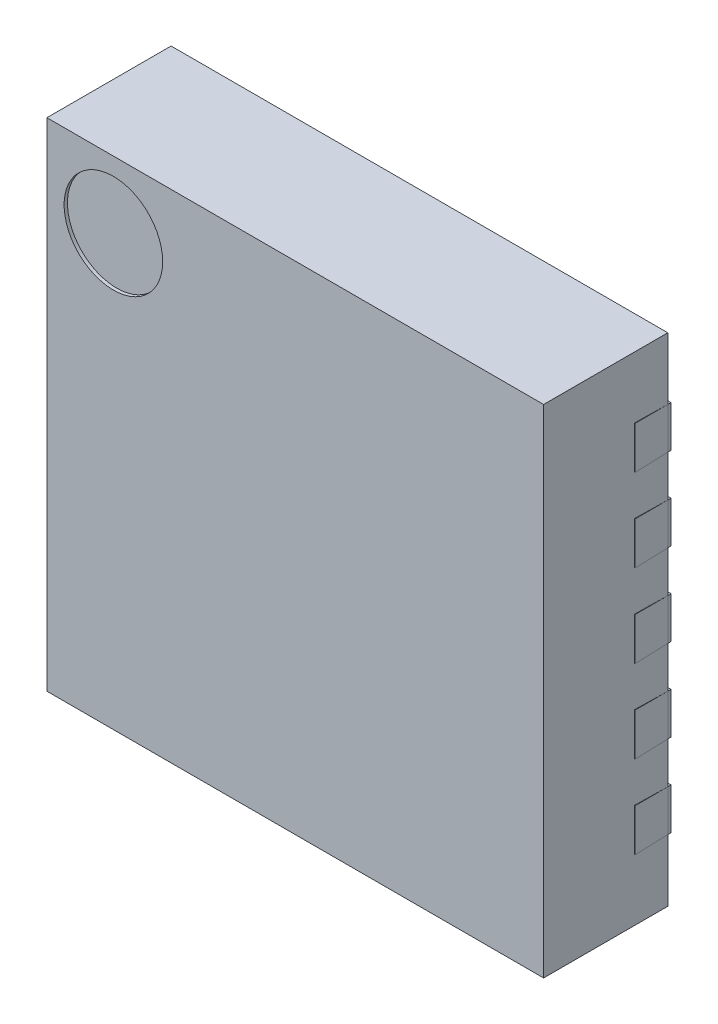
SolidWorks part; units mm, degrees
ref_plane "Front Plane" through (0, 0, 0) normal (0, 0, 1) x (1, 0, 0)
ref_plane "Top Plane" through (0, 0, 0) normal (0, 1, 0) x (1, 0, 0)
ref_plane "Right Plane" through (0, 0, 0) normal (1, 0, 0) x (0, 0, -1)
sketch "Sketch1" plane through (0, 0, 0) normal (0, 0, 1) x (1, 0, 0)
  line L1 (-1.5, -1.5) -> (1.5, -1.5)
  line L2 (-1.5, -1.5) -> (-1.5, 1.5)
  line L3 (-1.5, 1.5) -> (1.5, 1.5)
  line L4 (1.5, -1.5) -> (1.5, 1.5)
  line L5 (-1.5, -1.5) -> (1.5, 1.5) construction
  line L6 (-1.5, 1.5) -> (1.5, -1.5) construction
  point P0 (0, 0)
  dimension "D1" = 3
  dimension "D2" = 3
extrude "Boss-Extrude1" add sketch "Sketch1" along normal blind 0.75
sketch "Sketch2" plane through (0, 0, 0.75) normal (0, 0, 1) x (1, 0, 0)
  circle A0 centre (-1.0984, 1.0966) radius 0.2976
  point P2 (-1.0984, 1.0966)
extrude "Cut-Extrude1" cut sketch "Sketch2" against normal blind 0.02
sketch "Sketch3" plane through (0, 0, 0) normal (0, 0, -1) x (-1, 0, 0)
  line L0 (0.825, 1.0076) -> (0.6426, 1.19)
  line L1 (-0.825, -1.19) -> (0.825, -1.19)
  line L2 (-0.825, -1.19) -> (-0.825, 1.19)
  line L3 (-0.825, 1.19) -> (0.6426, 1.19)
  line L4 (0.825, -1.19) -> (0.825, 1.0076)
  line L5 (-0.825, -1.19) -> (0.7503, 1.0823) construction
  line L6 (-0.825, 1.19) -> (0.825, -1.19) construction
  point P0 (0, 0)
extrude "Boss-Extrude2" add sketch "Sketch3" along normal blind 0.02
sketch "Sketch4" plane through (0, 0, 0) normal (0, 0, -1) x (-1, 0, 0)
  line L0 (-1.5, -1.5) -> (-1.5, 1.5) construction
  line L1 (-1.5, 0.125) -> (-1.245, 0.125)
  line L3 (-1.5, -0.125) -> (-1.245, -0.125)
  line L5 (0, 0) -> (-1.5, 0) construction
  line L6 (-1.5, 0) -> (-1.12, 0) construction
  line L7 (-1.5, 0.125) -> (-1.5, -0.125)
  arc A0 (-1.245, -0.125) -> (-1.245, 0.125) centre (-1.245, 0) ccw
  point P0 (-1.5, 0)
  point P4 (-1.5, 0)
  dimension "D2" = 0.25
  dimension "D1" = 0.255
extrude "Boss-Extrude3" add sketch "Sketch4" along normal blind 0.02 and the other way blind 0.2 draft 1
pattern_linear "LPattern2" count 3 spacing 0.5 along (0, 1, 0) count 3 spacing 0.5 along (0, -1, 0) of "Boss-Extrude3"
mirror "Mirror1" about plane through (0, 0, 0) normal (1, 0, 0) of "LPattern2", "Boss-Extrude3"
